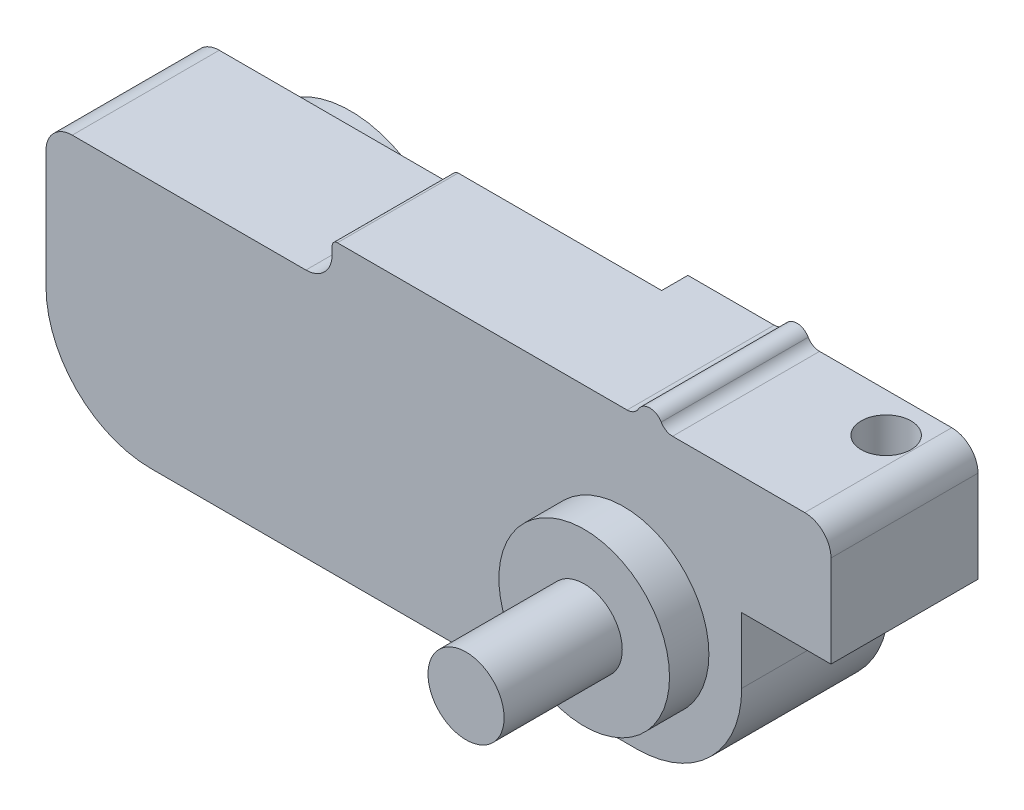
SolidWorks part; units mm, degrees
ref_plane "Front Plane" through (0, 0, 0) normal (0, 0, 1) x (1, 0, 0)
ref_plane "Top Plane" through (0, 0, 0) normal (0, 1, 0) x (1, 0, 0)
ref_plane "Right Plane" through (0, 0, 0) normal (1, 0, 0) x (0, 0, -1)
sketch "Sketch1" plane through (0, 0, 0) normal (0, 0, 1) x (1, 0, 0)
  line L1 (29.0734, 5.4975) -> (58.9734, 5.4975)
  line L2 (29.0734, 5.4975) -> (29.0734, -5.5025)
  line L3 (29.0734, -5.5025) -> (58.9734, -5.5025)
  line L4 (58.9734, 5.4975) -> (58.9734, -5.5025)
  dimension "D1" = 11
  dimension "D2" = 29.9
extrude "Boss-Extrude1" add sketch "Sketch1" along normal blind 5.6
sketch "Sketch2" plane through (0, 0, 0) normal (0, 0, -1) x (-1, 0, 0)
  line L0 (-29.0734, 5.4975) -> (-29.0734, -5.5025) construction
  line L1 (-29.0734, -5.5025) -> (-58.9734, -5.5025) construction
  circle A0 centre (-33.0734, -1.5025) radius 4
  dimension "D1" = 8
  dimension "D2" = 4
  dimension "D3" = 4
extrude "Boss-Extrude2" add sketch "Sketch2" along normal blind 2
sketch "Sketch4" plane through (0, 0, 0) normal (0, 0, -1) x (-1, 0, 0)
  line L0 (-29.0734, -1.5025) -> (-29.0734, -5.5025)
  line L1 (-29.0734, -5.5025) -> (-33.0734, -5.5025)
  arc A0 (-29.0734, -1.5025) -> (-33.0734, -5.5025) centre (-33.0734, -1.5025) cw
extrude "Cut-Extrude1" cut sketch "Sketch4" against normal blind 5.6
sketch "Sketch5" plane through (0, 0, 5.6) normal (0, 0, 1) x (1, 0, 0)
  line L0 (33.0734, -5.5025) -> (58.9734, -5.5025) construction
  circle A0 centre (51.0734, -1.0025) radius 3.25
  arc A1 (29.0734, -1.5025) -> (33.0734, -5.5025) centre (33.0734, -1.5025) ccw construction
  dimension "D1" = 6.5
  dimension "D2" = 18
  dimension "D3" = 4.5
extrude "Boss-Extrude3" add sketch "Sketch5" along normal blind 1.5
sketch "Sketch6" plane through (0, 0, 7.1) normal (0, 0, 1) x (1, 0, 0)
  circle A0 centre (51.0734, -1.0025) radius 1.45
  dimension "D1" = 2.9
extrude "Boss-Extrude4" add sketch "Sketch6" along normal blind 4.5
sketch "Sketch7" plane through (0, 0, 5.6) normal (0, 0, 1) x (1, 0, 0)
  line L0 (29.0734, 5.4975) -> (29.0734, -1.5025) construction
  line L1 (58.9734, -5.5025) -> (55.5734, -5.5025)
  line L2 (58.9734, -5.5025) -> (58.9734, 0.9975)
  line L3 (58.9734, 0.9975) -> (55.5734, 0.9975)
  line L4 (55.5734, -5.5025) -> (55.5734, 0.9975)
  dimension "D1" = 26.5
  dimension "D2" = 6.5
extrude "Cut-Extrude2" cut sketch "Sketch7" against normal blind 5.6
fillet "Fillet2" radius 4 1 edges at (55.5734, -5.5025, 2.8)
sketch "Sketch8" plane through (0, 0, 5.6) normal (0, 0, 1) x (1, 0, 0)
  line L0 (58.9734, 5.4975) -> (29.0734, 5.4975) construction
  circle A0 centre (52.0734, 5.4975) radius 0.5
  circle A1 centre (51.0734, -1.0025) radius 3.25 construction
  dimension "D1" = 1
  dimension "D2" = 1
extrude "Boss-Extrude5" add sketch "Sketch8" against normal blind 5.6
fillet "Fillet3" radius 0.5 2 edges at (52.5734, 5.4975, 2.8) (51.5734, 5.4975, 2.8)
sketch "Sketch9" plane through (0, 0.9975, 0) normal (0, -1, 0) x (1, 0, 0)
  line L0 (58.9734, 0) -> (55.5734, 0) construction
  line L1 (58.9734, 0) -> (58.9734, 5.6) construction
  circle A0 centre (56.9734, 1.5) radius 0.95
  dimension "D1" = 1.9
  dimension "D2" = 1.5
  dimension "D3" = 2
extrude "Cut-Extrude3" cut sketch "Sketch9" against normal up to surface (4.5 mm away) up to face at (55.9564, 5.4975, 2.8)
fillet "Fillet5" radius 1 1 edges at (58.9734, 5.4975, 2.8)
sketch "Sketch10" plane through (0, 0, 5.6) normal (0, 0, 1) x (1, 0, 0)
  line L1 (29.0734, 5.4975) -> (39.9734, 5.4975)
  line L2 (29.0734, 5.4975) -> (29.0734, 3.9975)
  line L3 (29.0734, 3.9975) -> (39.9734, 3.9975)
  line L4 (39.9734, 5.4975) -> (39.9734, 3.9975)
  dimension "D1" = 10.9
  dimension "D2" = 1.5
extrude "Cut-Extrude4" cut sketch "Sketch10" against normal blind 5.6
fillet "Fillet6" radius 1 1 edges at (29.0734, 3.9975, 2.8)
fillet "Fillet7" radius 1 1 edges at (39.9734, 3.9975, 2.8)
fillet "Fillet8" radius 0.2 1 edges at (39.9734, 5.4975, 2.8)
sketch "Sketch11" plane through (0, 0, 0) normal (0, 0, -1) x (-1, 0, 0)
  line L0 (-51.2074, 5.4975) -> (-40.1734, 5.4975) construction
  line L1 (-47.9234, 5.4975) -> (-38.7234, 5.4975)
  line L2 (-47.9234, 5.4975) -> (-47.9234, 1.7975)
  line L3 (-47.9234, 1.7975) -> (-38.7234, 1.7975)
  line L4 (-38.7234, 5.4975) -> (-38.7234, 1.7975)
  line L5 (-29.0734, 2.9975) -> (-29.0734, -1.5025) construction
  dimension "D1" = 9.65
  dimension "D2" = 3.7
  dimension "D3" = 9.2
extrude "Cut-Extrude5" cut sketch "Sketch11" against normal blind 1
fillet "Fillet9" radius 2 1 edges at (47.9234, 1.7975, 0.5)
sketch "Sketch12" plane through (0, 0, 0) normal (0, 0, -1) x (-1, 0, 0)
  line L0 (-37.0734, -1.5025) -> (-38.7444, -1.5025)
  line L1 (-38.7444, -1.5025) -> (-38.7444, -4.0804)
  line L2 (-38.7444, -4.0804) -> (-36.5375, -3.5025)
  line L3 (-33.0734, -5.5025) -> (-51.5734, -5.5025) construction
  arc A0 (-37.0734, -1.5025) -> (-36.5375, -3.5025) centre (-33.0734, -1.5025) ccw
  circle A1 centre (-33.0734, -1.5025) radius 4 construction
  dimension "D1" = 4
  dimension "D2" = 2
extrude "Boss-Extrude6" add sketch "Sketch12" along normal blind 0.4
fillet "Fillet10" radius 1 2 edges at (38.7444, -4.0804, -0.2) (38.7444, -1.5025, -0.2)
